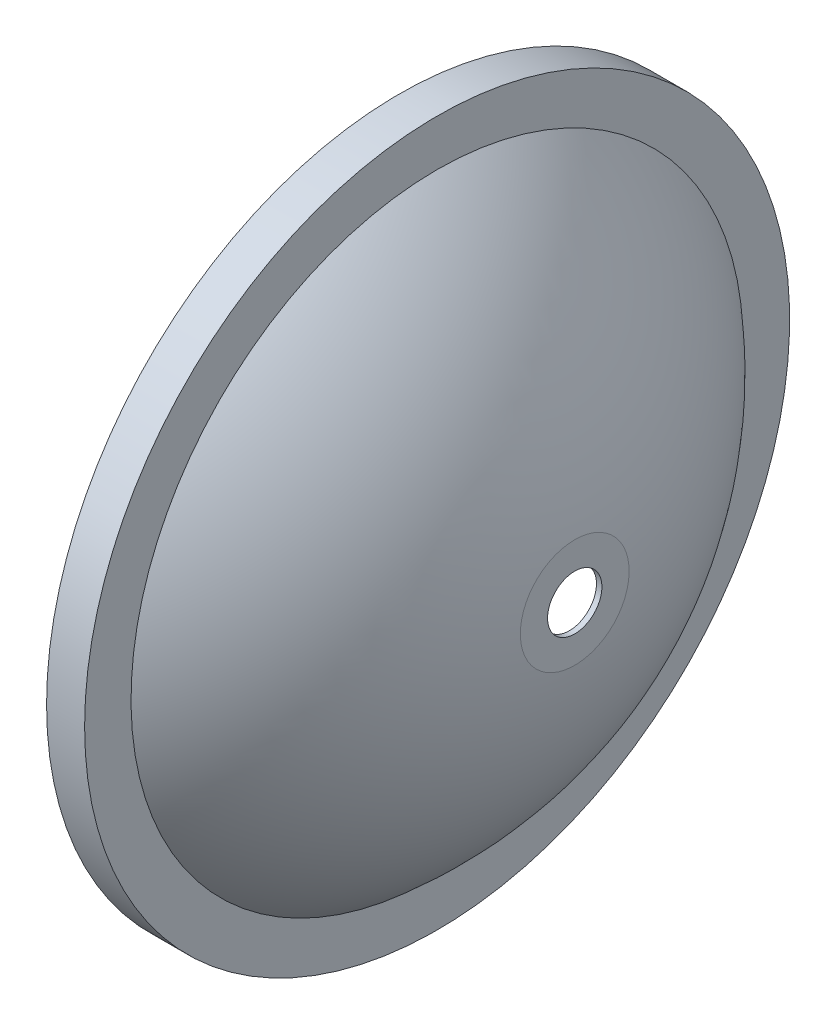
SolidWorks part; units mm, degrees
ref_plane "Płaszczyzna przednia" through (0, 0, 0) normal (0, 0, 1) x (1, 0, 0)
ref_plane "Płaszczyzna górna" through (0, 0, 0) normal (0, 1, 0) x (1, 0, 0)
ref_plane "Płaszczyzna prawa" through (0, 0, 0) normal (1, 0, 0) x (0, 0, -1)
sketch "Szkic1" plane through (0, 0, 0) normal (0, 0, 1) x (1, 0, 0)
  line L0 (-67.8554, 0) -> (33.0858, 0) construction
  line L1 (-31.3199, 63.857) -> (-25.3199, 63.857)
  line L2 (-25.3199, 55.857) -> (-25.3199, 63.857)
  line L3 (0, 5) -> (0, 9.9412)
  line L4 (-31.3199, 64.857) -> (-24.3199, 64.857)
  line L5 (-24.3199, 56.3205) -> (-24.3199, 64.857)
  line L6 (1, 5) -> (1, 10.0094)
  line L7 (-31.3199, 64.857) -> (-31.3199, 63.857)
  line L8 (0, 5) -> (1, 5)
  arc A0 (-25.3199, 55.857) -> (0, 9.9412) centre (-72.3199, 0) cw
  arc A1 (-24.3199, 56.3205) -> (1, 10.0094) centre (-72.3199, 0) cw
  dimension "D6" = 73
  dimension "D1" = 6
  dimension "D2" = 8
  dimension "D3" = 4.9412
  dimension "D4" = 5
  dimension "D5" = 41
  dimension "D7" = 1
revolve "Obrót1" add sketch "Szkic1" angle 360 about L0
